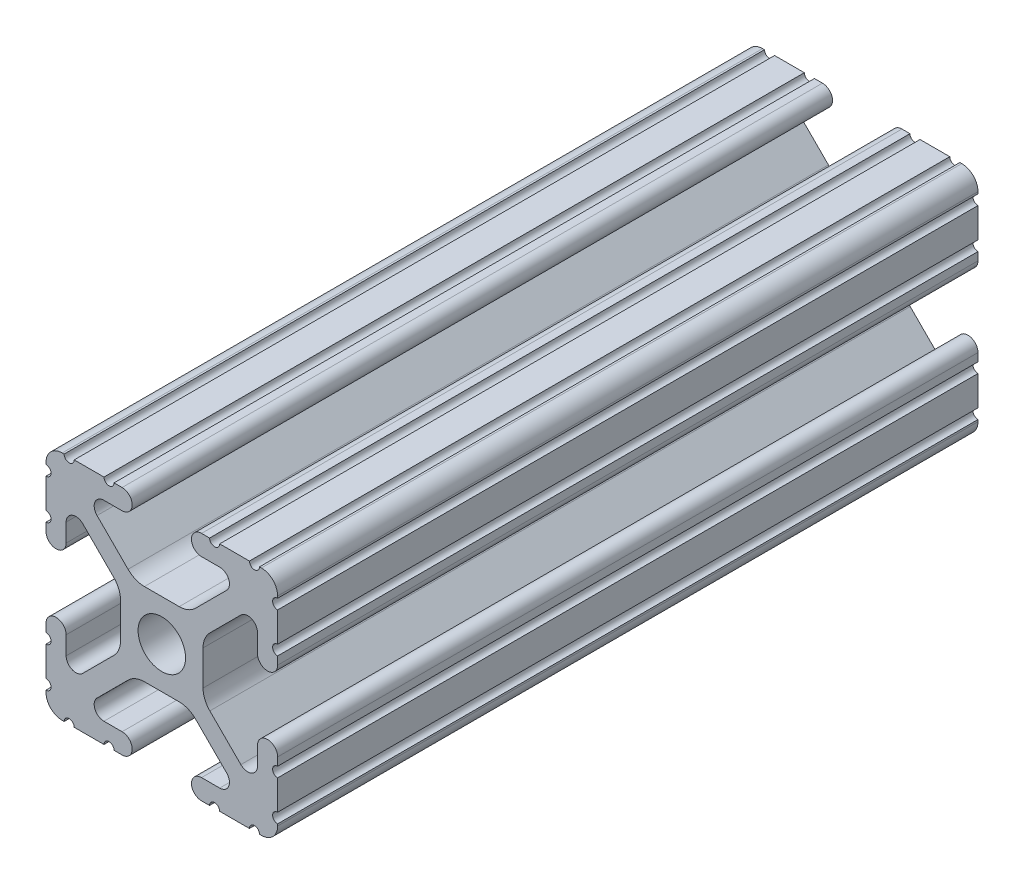
SolidWorks part; units mm, degrees
ref_plane "Front Plane" through (0, 0, 0) normal (0, 0, 1) x (1, 0, 0)
ref_plane "Top Plane" through (0, 0, 0) normal (0, 1, 0) x (1, 0, 0)
ref_plane "Right Plane" through (0, 0, 0) normal (1, 0, 0) x (0, 0, -1)
sketch "Sketch1" plane through (0, 0, 0) normal (0, 0, 1) x (1, 0, 0)
  line L0 (0, -12.7) -> (0, 12.7) construction
  line L1 (12.7, 0) -> (-12.7, 0) construction
  line L2 (3.2512, 12.7) -> (-3.2512, 12.7) construction
  line L3 (0, -4.5212) -> (0, 4.5212) construction
  line L4 (-3.2512, 12.7) -> (-3.2512, 10.4902) construction
  line L5 (12.7, -7.4168) -> (12.7, 7.4168) construction
  line L6 (0, -2.6035) -> (0, 2.6035) construction
  point P4 (0, 0)
  point P8 (0, 0)
  point P11 (0, 12.7)
  point P14 (0, 0)
  point P18 (12.7, 0)
  point P21 (0, 0)
sketch "Sketch2" plane through (0, 0, 0) normal (1, 0, 0) x (0, 0, -1)
  line L0 (-457.2, 0) -> (457.2, 0) construction
  point P4 (0, 0)
  dimension "Length" = 914.4
sketch "Sketch3" plane through (0, 0, 0) normal (0, 0, 1) x (1, 0, 0)
  line L1 (12.7, -12.7) -> (-12.7, -12.7)
  line L2 (12.7, -12.7) -> (12.7, 12.7)
  line L3 (12.7, 12.7) -> (-12.7, 12.7)
  line L4 (-12.7, -12.7) -> (-12.7, 12.7)
  line L5 (12.7, -12.7) -> (-12.7, 12.7) construction
  line L6 (12.7, 12.7) -> (-12.7, -12.7) construction
  point P0 (0, 0)
extrude "Boss-Extrude1" add sketch "Sketch3" along normal blind 76.8
sketch "Sketch4" plane through (0, 0, 76.8) normal (0, 0, 1) x (1, 0, 0)
  line L0 (-3.2512, 12.7) -> (-3.2512, 10.4902)
  line L1 (-3.2512, 10.4902) -> (-8.9276, 10.4902)
  line L2 (-8.9276, 10.4902) -> (-2.9586, 4.5212)
  line L3 (-2.9586, 4.5212) -> (2.9586, 4.5212)
  line L4 (0, -12.7) -> (0, 12.7) construction
  line L5 (12.7, 12.7) -> (-12.7, 12.7) construction
  line L6 (0, 12.7) -> (0, -12.7) construction
  line L7 (-12.7, 0) -> (12.7, 0) construction
  line L8 (-12.7, 12.7) -> (0, 0) construction
  line L9 (-12.7, 3.2512) -> (-10.4902, 3.2512)
  line L10 (-10.4902, 3.2512) -> (-10.4902, 8.9276)
  line L11 (-10.4902, 8.9276) -> (-4.5212, 2.9586)
  line L12 (-4.5212, 2.9586) -> (-4.5212, -2.9586)
  line L13 (4.5212, 2.9586) -> (4.5212, -2.9586)
  line L14 (10.4902, 8.9276) -> (4.5212, 2.9586)
  line L15 (10.4902, 3.2512) -> (10.4902, 8.9276)
  line L16 (12.7, 3.2512) -> (10.4902, 3.2512)
  line L17 (8.9276, 10.4902) -> (2.9586, 4.5212)
  line L18 (3.2512, 10.4902) -> (8.9276, 10.4902)
  line L19 (3.2512, 12.7) -> (3.2512, 10.4902)
  line L20 (3.2512, -12.7) -> (3.2512, -10.4902)
  line L21 (3.2512, -10.4902) -> (8.9276, -10.4902)
  line L22 (8.9276, -10.4902) -> (2.9586, -4.5212)
  line L23 (12.7, -3.2512) -> (10.4902, -3.2512)
  line L24 (10.4902, -3.2512) -> (10.4902, -8.9276)
  line L25 (10.4902, -8.9276) -> (4.5212, -2.9586)
  line L26 (-10.4902, -8.9276) -> (-4.5212, -2.9586)
  line L27 (-10.4902, -3.2512) -> (-10.4902, -8.9276)
  line L28 (-12.7, -3.2512) -> (-10.4902, -3.2512)
  line L29 (-2.9586, -4.5212) -> (2.9586, -4.5212)
  line L30 (-8.9276, -10.4902) -> (-2.9586, -4.5212)
  line L31 (-3.2512, -10.4902) -> (-8.9276, -10.4902)
  line L32 (-3.2512, -12.7) -> (-3.2512, -10.4902)
  line L33 (-12.7, 3.2512) -> (-12.7, -3.2512)
  line L34 (-3.2512, -12.7) -> (3.2512, -12.7)
  line L35 (12.7, -3.2512) -> (12.7, 3.2512)
  line L36 (3.2512, 12.7) -> (-3.2512, 12.7)
  line L37 (-12.7, 12.7) -> (-12.7, -12.7) construction
  line L38 (-12.7, -12.7) -> (12.7, -12.7) construction
  arc A3 (-6.3485, 10.4902) -> (-7.1039, 8.6665) centre (-6.3485, 9.4219) ccw
  arc A4 (7.1039, 8.6665) -> (6.3485, 10.4902) centre (6.3485, 9.4219) ccw
  arc A5 (8.6665, -7.1039) -> (10.4902, -6.3485) centre (9.4219, -6.3485) ccw
  arc A6 (10.4902, 6.3485) -> (8.6665, 7.1039) centre (9.4219, 6.3485) ccw
  arc A7 (-7.1039, -8.6665) -> (-6.3485, -10.4902) centre (-6.3485, -9.4219) ccw
  arc A8 (6.3485, -10.4902) -> (7.1039, -8.6665) centre (6.3485, -9.4219) ccw
  arc A9 (-8.6665, 7.1039) -> (-10.4902, 6.3485) centre (-9.4219, 6.3485) ccw
  arc A10 (-10.4902, -6.3485) -> (-8.6665, -7.1039) centre (-9.4219, -6.3485) ccw
  circle A11 centre (0, 0) radius 2.6035
  point P34 (0, 4.5212)
  point P45 (4.5212, 0)
  point P46 (-4.5212, 0)
  point P53 (0, -4.5212)
  point P81 (0, 0)
  line M2 (-12.7, 12.7) -> (-12.7, -12.7)
  line M3 (-12.7, -12.7) -> (12.7, -12.7)
  line M4 (12.7, -12.7) -> (12.7, 12.7)
  line M5 (12.7, 12.7) -> (-12.7, 12.7)
  dimension "D5" = 5.207
  dimension "D1" = 2.2098
  dimension "D2" = 2.2098
  dimension "D3" = 14.8336
  dimension "D4" = 4
extrude "Cut-Extrude1" cut sketch "Sketch4" against normal through all contours L17 A4 L18 L19 L0 L1 A3 L2 L3 M5 | L15 A6 L14 L13 L25 A5 L24 L23 L16 M4 | L21 A8 L22 L29 L30 A7 L31 L32 L20 M3 | L27 A10 L26 L12 L11 A9 L10 L9 L28 M2 | A11
sketch "Sketch5" plane through (0, 0, 76.8) normal (0, 0, 1) x (1, 0, 0)
  line L0 (-4.3561, 12.7) -> (-3.2512, 12.7)
  line L1 (-3.2512, 12.7) -> (-3.2512, 10.4902)
  line L2 (-3.2512, 10.4902) -> (-4.3561, 10.4902)
  line L3 (0, -12.7) -> (0, 12.7) construction
  line L4 (-3.2512, 12.7) -> (-12.7, 12.7) construction
  line L5 (3.2512, 10.4902) -> (4.3561, 10.4902)
  line L6 (3.2512, 12.7) -> (3.2512, 10.4902)
  line L7 (4.3561, 12.7) -> (3.2512, 12.7)
  line L8 (12.7, 4.3561) -> (12.7, 3.2512)
  line L9 (12.7, 3.2512) -> (10.4902, 3.2512)
  line L10 (10.4902, 3.2512) -> (10.4902, 4.3561)
  line L11 (10.4902, -3.2512) -> (10.4902, -4.3561)
  line L12 (12.7, -3.2512) -> (10.4902, -3.2512)
  line L13 (12.7, -4.3561) -> (12.7, -3.2512)
  line L14 (4.3561, -12.7) -> (3.2512, -12.7)
  line L15 (3.2512, -12.7) -> (3.2512, -10.4902)
  line L16 (3.2512, -10.4902) -> (4.3561, -10.4902)
  line L17 (-3.2512, -10.4902) -> (-4.3561, -10.4902)
  line L18 (-3.2512, -12.7) -> (-3.2512, -10.4902)
  line L19 (-4.3561, -12.7) -> (-3.2512, -12.7)
  line L20 (-12.7, -4.3561) -> (-12.7, -3.2512)
  line L21 (-12.7, -3.2512) -> (-10.4902, -3.2512)
  line L22 (-10.4902, -3.2512) -> (-10.4902, -4.3561)
  line L23 (-10.4902, 3.2512) -> (-10.4902, 4.3561)
  line L24 (-12.7, 3.2512) -> (-10.4902, 3.2512)
  line L25 (-12.7, 4.3561) -> (-12.7, 3.2512)
  line L26 (-12.7, 12.7) -> (-12.7, 3.2512) construction
  line L27 (-10.7124, 12.7) -> (-9.6075, 12.7)
  line L28 (-6.3436, 12.7) -> (-5.2387, 12.7)
  line L29 (-12.7, 10.7124) -> (-12.7, 9.6075)
  line L30 (-12.7, 6.3436) -> (-12.7, 5.2387)
  line L31 (6.3437, 12.7) -> (5.2388, 12.7)
  line L32 (10.7125, 12.7) -> (9.6076, 12.7)
  line L33 (12.7, 10.7125) -> (12.7, 9.6075)
  line L34 (12.7, 6.3436) -> (12.7, 5.2387)
  line L35 (12.7, -6.3437) -> (12.7, -5.2388)
  line L36 (12.7, -10.7125) -> (12.7, -9.6076)
  line L37 (10.7125, -12.7) -> (9.6076, -12.7)
  line L38 (6.3437, -12.7) -> (5.2388, -12.7)
  line L39 (-6.3436, -12.7) -> (-5.2387, -12.7)
  line L40 (-10.7124, -12.7) -> (-9.6075, -12.7)
  line L41 (-12.7, -10.7125) -> (-12.7, -9.6076)
  line L42 (-12.7, -6.3437) -> (-12.7, -5.2388)
  line L43 (12.7, 12.7) -> (3.2512, 12.7) construction
  line L44 (12.7, 3.2512) -> (12.7, 12.7) construction
  arc A0 (-4.3561, 10.4902) -> (-4.3561, 12.7) centre (-4.3561, 11.5951) ccw
  arc A1 (4.3561, 10.4902) -> (4.3561, 12.7) centre (4.3561, 11.5951) cw
  arc A2 (10.4902, 4.3561) -> (12.7, 4.3561) centre (11.5951, 4.3561) ccw
  arc A3 (10.4902, -4.3561) -> (12.7, -4.3561) centre (11.5951, -4.3561) cw
  arc A4 (4.3561, -10.4902) -> (4.3561, -12.7) centre (4.3561, -11.5951) ccw
  arc A5 (-4.3561, -10.4902) -> (-4.3561, -12.7) centre (-4.3561, -11.5951) cw
  arc A6 (-10.4902, -4.3561) -> (-12.7, -4.3561) centre (-11.5951, -4.3561) ccw
  arc A7 (-10.4902, 4.3561) -> (-12.7, 4.3561) centre (-11.5951, 4.3561) cw
  arc A8 (-10.7124, 12.7) -> (-9.6075, 12.7) centre (-10.16, 12.7) ccw
  arc A9 (-6.3436, 12.7) -> (-5.2387, 12.7) centre (-5.7912, 12.7) ccw
  arc A10 (-12.7, 9.6075) -> (-12.7, 10.7124) centre (-12.7, 10.16) ccw
  arc A11 (-12.7, 5.2387) -> (-12.7, 6.3436) centre (-12.7, 5.7912) ccw
  arc A12 (5.2388, 12.7) -> (6.3437, 12.7) centre (5.7912, 12.7) ccw
  arc A13 (9.6076, 12.7) -> (10.7125, 12.7) centre (10.16, 12.7) ccw
  arc A14 (12.7, 10.7125) -> (12.7, 9.6075) centre (12.7, 10.16) ccw
  arc A15 (12.7, 6.3436) -> (12.7, 5.2387) centre (12.7, 5.7912) ccw
  arc A16 (12.7, -5.2388) -> (12.7, -6.3437) centre (12.7, -5.7912) ccw
  arc A17 (12.7, -9.6076) -> (12.7, -10.7125) centre (12.7, -10.16) ccw
  arc A18 (10.7125, -12.7) -> (9.6076, -12.7) centre (10.16, -12.7) ccw
  arc A19 (6.3437, -12.7) -> (5.2388, -12.7) centre (5.7912, -12.7) ccw
  arc A20 (-5.2387, -12.7) -> (-6.3436, -12.7) centre (-5.7912, -12.7) ccw
  arc A21 (-9.6075, -12.7) -> (-10.7124, -12.7) centre (-10.16, -12.7) ccw
  arc A22 (-12.7, -10.7125) -> (-12.7, -9.6076) centre (-12.7, -10.16) ccw
  arc A23 (-12.7, -6.3437) -> (-12.7, -5.2388) centre (-12.7, -5.7912) ccw
  point P11 (0, 0)
  point P52 (0, 0)
  point P104 (0, 0)
  line M5 (3.2512, -10.4902) -> (3.2512, -12.7)
  line M6 (3.2512, -12.7) -> (12.7, -12.7)
  line M7 (12.7, -12.7) -> (12.7, -3.2512)
  line M8 (12.7, -3.2512) -> (10.4902, -3.2512)
  line M9 (10.4902, -3.2512) -> (10.4902, -6.3485)
  line M15 (10.4902, 6.3485) -> (10.4902, 3.2512)
  line M16 (10.4902, 3.2512) -> (12.7, 3.2512)
  line M17 (12.7, 3.2512) -> (12.7, 12.7)
  line M18 (12.7, 12.7) -> (3.2512, 12.7)
  line M19 (3.2512, 12.7) -> (3.2512, 10.4902)
  line M20 (3.2512, 10.4902) -> (6.3485, 10.4902)
  line M26 (-6.3485, 10.4902) -> (-3.2512, 10.4902)
  line M27 (-3.2512, 10.4902) -> (-3.2512, 12.7)
  line M28 (-3.2512, 12.7) -> (-12.7, 12.7)
  line M29 (-12.7, 12.7) -> (-12.7, 3.2512)
  line M30 (-12.7, 3.2512) -> (-10.4902, 3.2512)
  line M31 (-10.4902, 3.2512) -> (-10.4902, 6.3485)
  line M37 (-10.4902, -6.3485) -> (-10.4902, -3.2512)
  line M38 (-10.4902, -3.2512) -> (-12.7, -3.2512)
  line M39 (-12.7, -3.2512) -> (-12.7, -12.7)
  line M40 (-12.7, -12.7) -> (-3.2512, -12.7)
  line M41 (-3.2512, -12.7) -> (-3.2512, -10.4902)
  line M42 (-3.2512, -10.4902) -> (-6.3485, -10.4902)
  line M48 (6.3485, -10.4902) -> (3.2512, -10.4902)
  dimension "D2" = 0.5524
  dimension "D3" = 2.54
  dimension "D4" = 2.54
  dimension "D5" = 2.54
  dimension "D6" = 2.54
  dimension "D1" = 4
  dimension "D7" = 4
extrude "Cut-Extrude2" cut sketch "Sketch5" against normal through all contours A7 M30 M29 | A7 L24 M31 | A6 L21 M39 | A6 M37 M38 | A5 L18 M42 | A5 M41 M40 | A4 M48 M5 | A4 L15 M6 | A3 L12 M9 | A3 M8 M7 | A2 M15 M16 | A2 L9 M17 | A1 M19 M18 | A1 L6 M20 | A0 L1 M28 | A0 M26 M27 | A11 L30 | A10 L29 | A8 L27 | A9 L28 | L31 A12 | L32 A13 | L33 A14 | L34 A15 | L42 A23 | L41 A22 | L40 A21 | L39 A20 | L36 A17 | L35 A16 | L37 A18 | L38 A19
fillet "Fillet1" radius 2.54 8 edges at (2.9586, -4.5212, 38.4) (-2.9586, -4.5212, 38.4) (4.5212, -2.9586, 38.4) (4.5212, 2.9586, 38.4) (-2.9586, 4.5212, 38.4) (2.9586, 4.5212, 38.4) (-4.5212, -2.9586, 38.4) (-4.5212, 2.9586, 38.4)
fillet "Fillet2" radius 1.778 4 edges at (12.7, -12.7, 38.4) (12.7, 12.7, 38.4) (-12.7, -12.7, 38.4) (-12.7, 12.7, 38.4)
equation "\"D2@Sketch4\"=\"Thickness@Sketch1\""
equation "\"D1@Sketch4\"=\"Thickness@Sketch1\""
equation "\"D3@Sketch4\"=\"Opening Width@Sketch1\""
equation "\"D5@Sketch4\"=\"Hole Dia@Sketch1\""
equation "\"D2@Sketch5\"=\"Thickness@Sketch1\"/4"
equation "\"D3@Sketch5\"=\"Height@Sketch1\"/10"
equation "\"D4@Sketch5\"=\"D3@Sketch5\""
equation "\"D5@Sketch5\"=\"D4@Sketch5\""
equation "\"D6@Sketch5\"=\"D5@Sketch5\""
